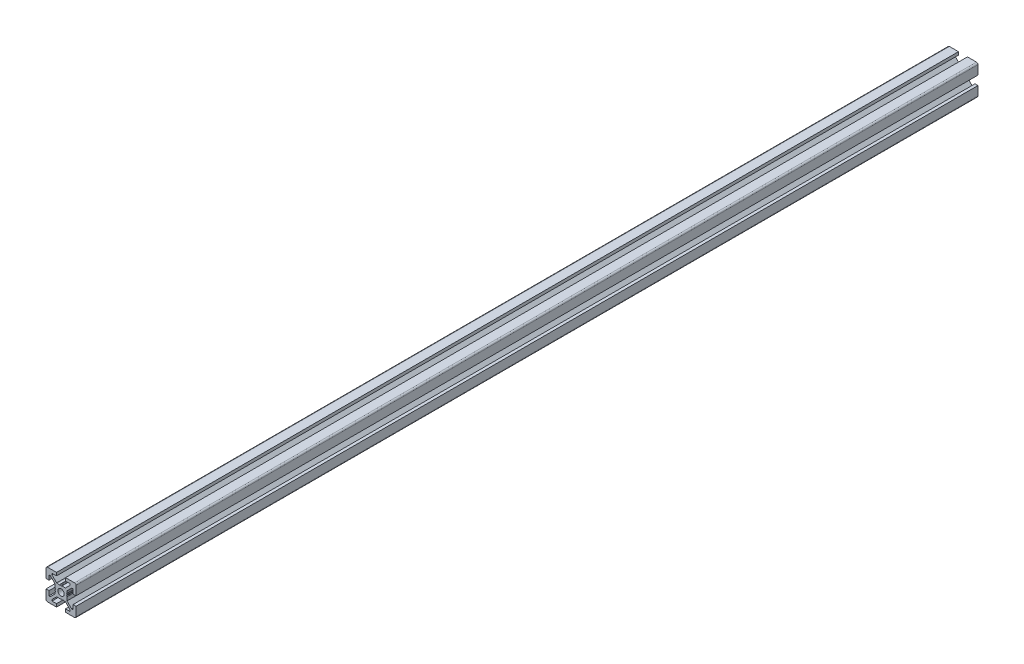
SolidWorks part; units mm, degrees
ref_plane "Front Plane" through (0, 0, 0) normal (0, 0, 1) x (1, 0, 0)
ref_plane "Top Plane" through (0, 0, 0) normal (0, 1, 0) x (1, 0, 0)
ref_plane "Right Plane" through (0, 0, 0) normal (1, 0, 0) x (0, 0, -1)
ref_plane "Plane1" through (0, 0, -2000) normal (0, 0, -1) x (-1, 0, 0)
sketch "Sketch1" plane through (0, 0, -2000) normal (0, 0, -1) x (-1, 0, 0)
  line L0 (10, -3) -> (8, -3)
  line L1 (8, -3) -> (8, -6)
  line L2 (8, -6) -> (7.0607, -6)
  line L3 (7.0607, -6) -> (4, -2.9393)
  line L4 (4, -2.9393) -> (4, -2.5)
  line L5 (4, -2.5) -> (3.751, -1.2189)
  line L6 (3.751, -1.2189) -> (3.933, -0.9036)
  line L7 (3.933, -0.4036) -> (3.7, 0)
  line L8 (3.7, 0) -> (3.933, 0.4036)
  line L9 (4, 0.6536) -> (4, 2.9393)
  line L10 (4, 2.9393) -> (7.0607, 6)
  line L11 (7.0607, 6) -> (8, 6)
  line L12 (8, 6) -> (8, 3)
  line L13 (8, 3) -> (10, 3)
  line L14 (10, 3) -> (10, 9)
  line L15 (9, 10) -> (3, 10)
  line L16 (3, 10) -> (3, 8)
  line L17 (3, 8) -> (6, 8)
  line L18 (6, 8) -> (6, 7.0607)
  line L19 (6, 7.0607) -> (2.9393, 4)
  line L20 (2.9393, 4) -> (2.5, 4)
  line L21 (2.5, 4) -> (1.2189, 3.751)
  line L22 (1.2189, 3.751) -> (0.9036, 3.933)
  line L23 (0.4036, 3.933) -> (0, 3.7)
  line L24 (0, 3.7) -> (-0.4036, 3.933)
  line L25 (-0.6536, 4) -> (-2.9393, 4)
  line L26 (-2.9393, 4) -> (-6, 7.0607)
  line L27 (-6, 7.0607) -> (-6, 8)
  line L28 (-6, 8) -> (-3, 8)
  line L29 (-3, 8) -> (-3, 10)
  line L30 (-3, 10) -> (-9, 10)
  line L31 (-10, 9) -> (-10, 3)
  line L32 (-10, 3) -> (-8, 3)
  line L33 (-8, 3) -> (-8, 6)
  line L34 (-8, 6) -> (-7.0607, 6)
  line L35 (-7.0607, 6) -> (-4, 2.9393)
  line L36 (-4, 2.9393) -> (-4, 2.5)
  line L37 (-4, 2.5) -> (-3.751, 1.2189)
  line L38 (-3.751, 1.2189) -> (-3.933, 0.9036)
  line L39 (-3.933, 0.4036) -> (-3.7, 0)
  line L40 (-3.7, 0) -> (-3.933, -0.4036)
  line L41 (-4, -0.6536) -> (-4, -2.9393)
  line L42 (-4, -2.9393) -> (-7.0607, -6)
  line L43 (-7.0607, -6) -> (-8, -6)
  line L44 (-8, -6) -> (-8, -3)
  line L45 (-8, -3) -> (-10, -3)
  line L46 (-10, -3) -> (-10, -9)
  line L47 (-9, -10) -> (-3, -10)
  line L48 (-3, -10) -> (-3, -8)
  line L49 (-3, -8) -> (-6, -8)
  line L50 (-6, -8) -> (-6, -7.0607)
  line L51 (-6, -7.0607) -> (-2.9393, -4)
  line L52 (-2.9393, -4) -> (-2.5, -4)
  line L53 (-2.5, -4) -> (-1.2189, -3.751)
  line L54 (-1.2189, -3.751) -> (-0.9036, -3.933)
  line L55 (-0.4036, -3.933) -> (0, -3.7)
  line L56 (0, -3.7) -> (0.4036, -3.933)
  line L57 (0.6536, -4) -> (2.9393, -4)
  line L58 (2.9393, -4) -> (6, -7.0607)
  line L59 (6, -7.0607) -> (6, -8)
  line L60 (6, -8) -> (3, -8)
  line L61 (3, -8) -> (3, -10)
  line L62 (3, -10) -> (9, -10)
  line L63 (10, -9) -> (10, -3)
  circle A0 centre (0, 0) radius 2.1
  arc A1 (3.933, -0.9036) -> (3.933, -0.4036) centre (3.5, -0.6536) ccw
  arc A2 (3.933, 0.4036) -> (4, 0.6536) centre (3.5, 0.6536) ccw
  arc A3 (10, 9) -> (9, 10) centre (9, 9) ccw
  arc A4 (0.9036, 3.933) -> (0.4036, 3.933) centre (0.6536, 3.5) ccw
  arc A5 (-0.4036, 3.933) -> (-0.6536, 4) centre (-0.6536, 3.5) ccw
  arc A6 (-9, 10) -> (-10, 9) centre (-9, 9) ccw
  arc A7 (-3.933, 0.9036) -> (-3.933, 0.4036) centre (-3.5, 0.6536) ccw
  arc A8 (-3.933, -0.4036) -> (-4, -0.6536) centre (-3.5, -0.6536) ccw
  arc A9 (-10, -9) -> (-9, -10) centre (-9, -9) ccw
  arc A10 (-0.9036, -3.933) -> (-0.4036, -3.933) centre (-0.6536, -3.5) ccw
  arc A11 (0.4036, -3.933) -> (0.6536, -4) centre (0.6536, -3.5) ccw
  arc A12 (9, -10) -> (10, -9) centre (9, -9) ccw
extrude "Boss-Extrude1" add sketch "Sketch1" against normal blind 600
